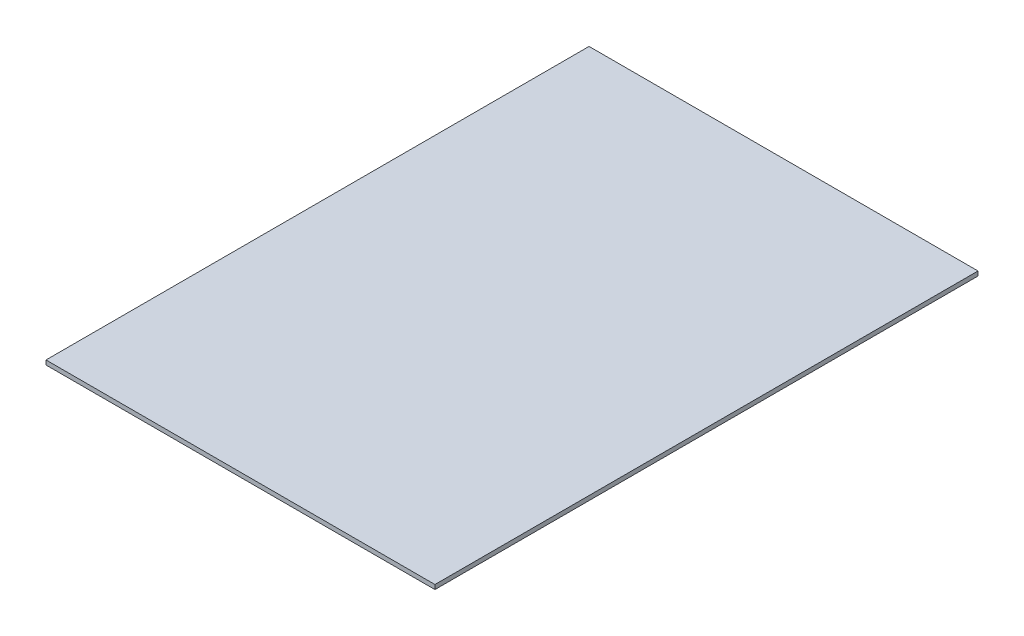
SolidWorks part; units mm, degrees
ref_plane "Front Plane" through (0, 0, 0) normal (0, 0, 1) x (1, 0, 0)
ref_plane "Top Plane" through (0, 0, 0) normal (0, 1, 0) x (1, 0, 0)
ref_plane "Right Plane" through (0, 0, 0) normal (1, 0, 0) x (0, 0, -1)
sketch "Sketch1" plane through (0, 0, 0) normal (0, 1, 0) x (1, 0, 0)
  line L1 (0, 0) -> (420.6875, 0)
  line L2 (0, 0) -> (0, 587.375)
  line L3 (0, 587.375) -> (420.6875, 587.375)
  line L4 (420.6875, 0) -> (420.6875, 587.375)
  dimension "D1" = 420.6875
  dimension "D2" = 587.375
extrude "Boss-Extrude1" add sketch "Sketch1" along normal blind 4.7625
